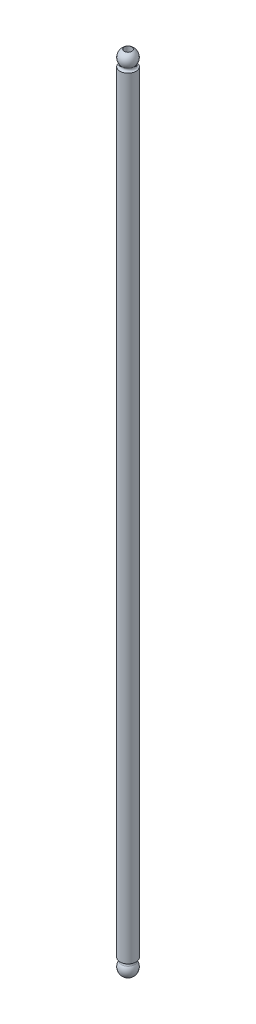
SolidWorks part; units mm, degrees
ref_plane "Front Plane" through (0, 0, 0) normal (0, 0, 1) x (1, 0, 0)
ref_plane "Top Plane" through (0, 0, 0) normal (0, 1, 0) x (1, 0, 0)
ref_plane "Right Plane" through (0, 0, 0) normal (1, 0, 0) x (0, 0, -1)
sketch "Sketch1" plane through (0, 0, 0) normal (0, 1, 0) x (1, 0, 0)
  circle A0 centre (0, 0) radius 3.175
  dimension "D1" = 6.35
extrude "Boss-Extrude1" add sketch "Sketch1" along normal mid plane 304.8
sketch "Sketch2" plane through (0, 0, 0) normal (0, 0, 1) x (1, 0, 0)
  line L0 (3.175, 152.4) -> (-3.175, 152.4) construction
  line L1 (0, 158.75) -> (0, 152.4) construction
  line L2 (3.175, 152.4) -> (-3.175, 152.4) construction
  line L3 (0, 158.75) -> (0, 152.4)
  line L4 (-3.175, 152.4) -> (0, 152.4)
  arc A0 (0, 158.75) -> (-2.54, 153.67) centre (0, 155.575) ccw
  arc A1 (-2.54, 153.67) -> (-3.175, 152.4) centre (-3.175, 153.1937) cw
  point P8 (0, 152.4)
  dimension "D1" = 6.35
revolve "Revolve1" add sketch "Sketch2" angle 360 about L3
mirror "Mirror1" about plane through (0, 0, 0) normal (0, 1, 0) of "Revolve1"
sketch "Sketch3" plane through (0, 0, 0) normal (0, 1, 0) x (1, 0, 0)
  circle A0 centre (0, 0) radius 3.175 construction
  circle A1 centre (0, 0) radius 3.175 construction
  circle A2 centre (0, 0) radius 1.4986
  dimension "D1" = 2.9972
extrude "Cut-Extrude1" cut sketch "Sketch3" against normal through all and the other way through all
